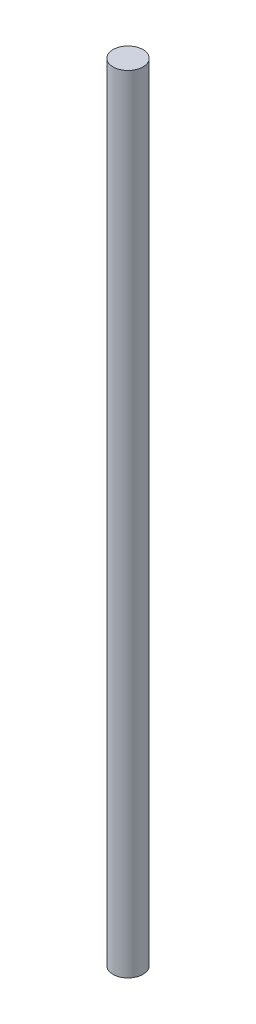
SolidWorks part; units mm, degrees
ref_plane "Front Plane" through (0, 0, 0) normal (0, 0, 1) x (1, 0, 0)
ref_plane "Top Plane" through (0, 0, 0) normal (0, 1, 0) x (1, 0, 0)
ref_plane "Right Plane" through (0, 0, 0) normal (1, 0, 0) x (0, 0, -1)
sketch "Sketch1" plane through (0, 0, 0) normal (0, 1, 0) x (1, 0, 0)
  circle A0 centre (0, 0) radius 2.9083
extrude "Boss-Extrude1" add sketch "Sketch1" along normal blind 152.4
